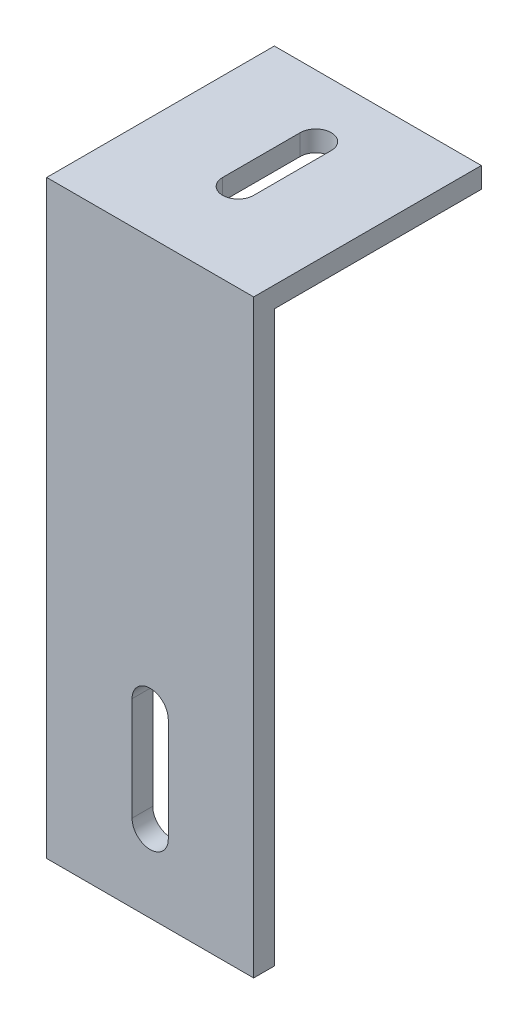
SolidWorks part; units mm, degrees
ref_plane "前视基准面" through (0, 0, 0) normal (0, 0, 1) x (1, 0, 0)
ref_plane "上视基准面" through (0, 0, 0) normal (0, 1, 0) x (1, 0, 0)
ref_plane "右视基准面" through (0, 0, 0) normal (1, 0, 0) x (0, 0, -1)
sketch "草图1" plane through (0, 0, 0) normal (1, 0, 0) x (0, 0, -1)
  line L0 (0, 0) -> (0, 114)
  line L1 (0, 114) -> (44, 114)
  line L2 (44, 114) -> (44, 110)
  line L3 (44, 110) -> (4, 110)
  line L4 (4, 110) -> (4, 0)
  line L5 (4, 0) -> (0, 0)
  dimension "D1" = 4
  dimension "D2" = 4
  dimension "D3" = 110
  dimension "D4" = 40
extrude "凸台-拉伸1" add sketch "草图1" along normal blind 40
sketch "草图2" plane through (0, 114, 0) normal (0, 1, 0) x (1, 0, 0)
  line L0 (17, 32) -> (17, 17)
  line L1 (23, 17) -> (23, 32)
  line L2 (40, 44) -> (0, 44) construction
  arc A0 (23, 32) -> (17, 32) centre (20, 32) ccw
  arc A1 (17, 17) -> (23, 17) centre (20, 17) ccw
  dimension "D2" = 6
  dimension "D3" = 6
  dimension "D4" = 12
  dimension "D1" = 15
extrude "切除-拉伸1" cut sketch "草图2" against normal up to next
sketch "草图3" plane through (0, 0, 0) normal (0, 0, 1) x (1, 0, 0)
  line L0 (23.5, 15) -> (23.5, 35)
  line L1 (16.5, 35) -> (16.5, 15)
  line L2 (40, 0) -> (0, 0) construction
  line L3 (0, 114) -> (0, 0) construction
  arc A0 (16.5, 15) -> (23.5, 15) centre (20, 15) ccw
  arc A1 (23.5, 35) -> (16.5, 35) centre (20, 35) ccw
  point P8 (20, 0)
  dimension "D2" = 15
  dimension "D3" = 3.5
  dimension "D4" = 20
  dimension "D1" = 20
extrude "切除-拉伸2" cut sketch "草图3" against normal up to next
